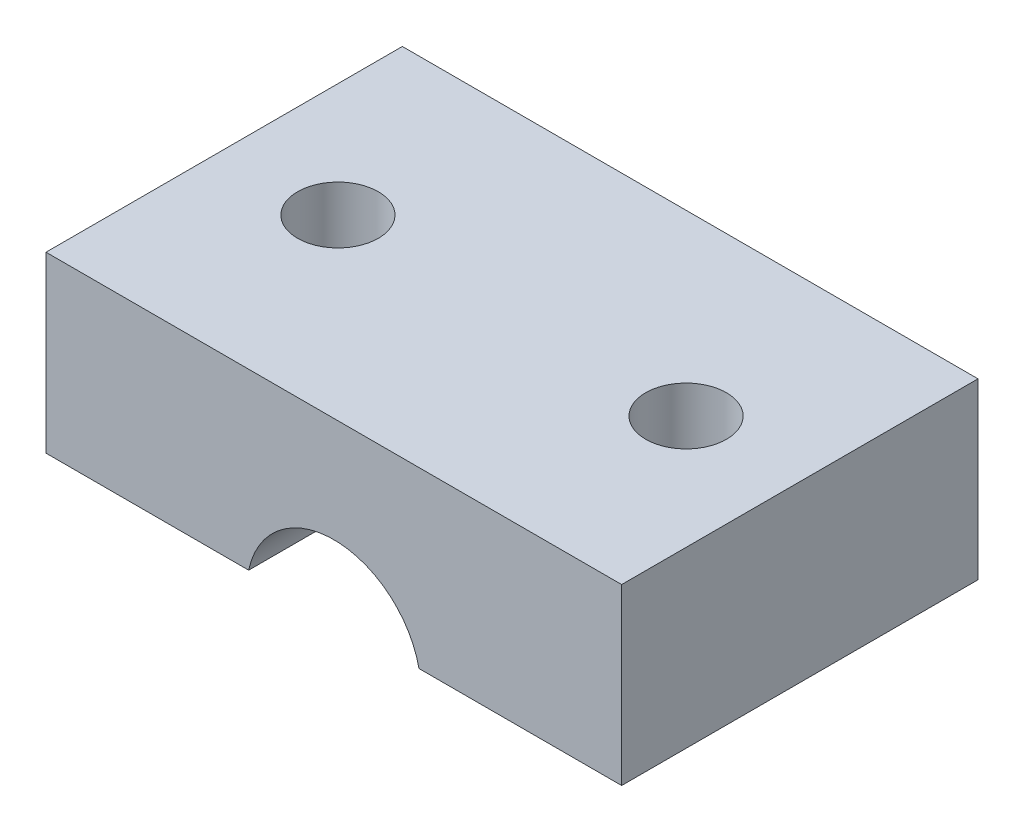
SolidWorks part; units mm, degrees
ref_plane "Front Plane" through (0, 0, 0) normal (0, 0, 1) x (1, 0, 0)
ref_plane "Top Plane" through (0, 0, 0) normal (0, 1, 0) x (1, 0, 0)
ref_plane "Right Plane" through (0, 0, 0) normal (1, 0, 0) x (0, 0, -1)
sketch "Sketch1" plane through (0, 0, 0) normal (0, 1, 0) x (1, 0, 0)
  line L0 (31, 0) -> (31, -13)
  line L1 (0, 0) -> (41, 0)
  line L2 (0, 0) -> (0, -13)
  line L3 (0, -13) -> (41, -13)
  line L4 (41, 0) -> (41, -13)
  line L5 (10, 0) -> (10, -13)
  circle A0 centre (14.15, -6.5) radius 1.4732
  circle A1 centre (26.85, -6.5) radius 1.4732
  point P5 (14.15, -6.5)
  point P6 (26.85, -6.5)
  dimension "D6" = 2.9464
  dimension "D1" = 41
  dimension "D2" = 13
  dimension "D3" = 6.5
  dimension "D4" = 14.15
  dimension "D5" = 12.7
  dimension "D7" = 10
  dimension "D8" = 10
extrude "Boss-Extrude1" add sketch "Sketch1" along normal blind 6.35 contours L1 L5 L3 L0 A1 A0
sketch "Sketch2" plane through (0, 0, 0) normal (0, 0, -1) x (-1, 0, 0)
  line L0 (-10, 0) -> (-31, 0) construction
  line L2 (-23.6064, 0) -> (-17.3936, 0)
  circle A0 centre (-20.5, -0.6563) radius 3.175
  point P6 (-20.5, 0)
  line M6 (-31, 0) -> (-10, 0)
  dimension "D1" = 6.35
  dimension "D2" = 6.2128
extrude "Cut-Extrude1" cut sketch "Sketch2" against normal up to surface (13 mm away) contours A0 M6 up to face at (20.5, 3.175, 13)
equation "\"D4@Sketch1\"=(41-12.7)/2"
equation "\"D8@Sketch1\"=\"D7@Sketch1\""
